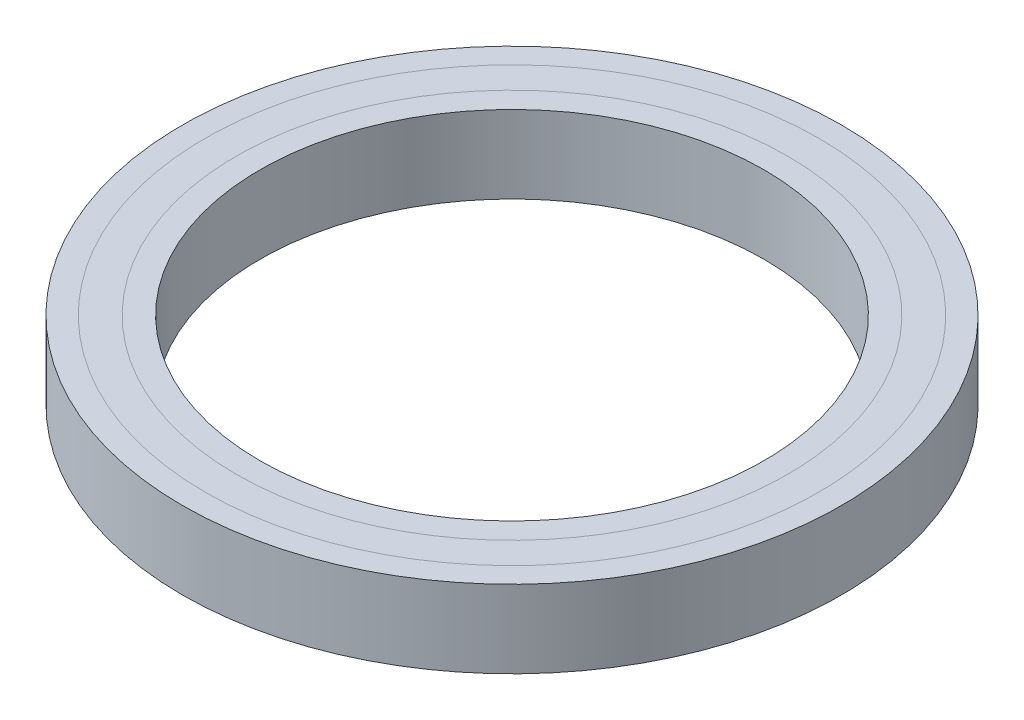
SolidWorks part; units mm, degrees
ref_plane "Front Plane" through (0, 0, 0) normal (0, 0, 1) x (1, 0, 0)
ref_plane "Top Plane" through (0, 0, 0) normal (0, 1, 0) x (1, 0, 0)
ref_plane "Right Plane" through (0, 0, 0) normal (1, 0, 0) x (0, 0, -1)
sketch "Sketch1" plane through (0, 0, 0) normal (0, 1, 0) x (1, 0, 0)
  circle A0 centre (0, 0) radius 32.5
  circle A1 centre (0, 0) radius 35.55
  dimension "D1" = 65
  dimension "D2" = 71.1
extrude "Boss-Extrude1" add sketch "Sketch1" along normal blind 10
sketch "Sketch2" plane through (0, 0, 0) normal (0, 1, 0) x (1, 0, 0)
  circle A0 centre (0, 0) radius 35.55
  circle A1 centre (0, 0) radius 39.55
  dimension "D1" = 79.1
  dimension "D2" = 71.1
extrude "Boss-Extrude2" add sketch "Sketch2" along normal blind 10 separate body
sketch "Sketch3" plane through (0, 0, 0) normal (0, 1, 0) x (1, 0, 0)
  circle A0 centre (0, 0) radius 39.55
  circle A1 centre (0, 0) radius 42.5
  dimension "D1" = 85
  dimension "D2" = 79.1
extrude "Boss-Extrude4" add sketch "Sketch3" along normal blind 10 separate body
